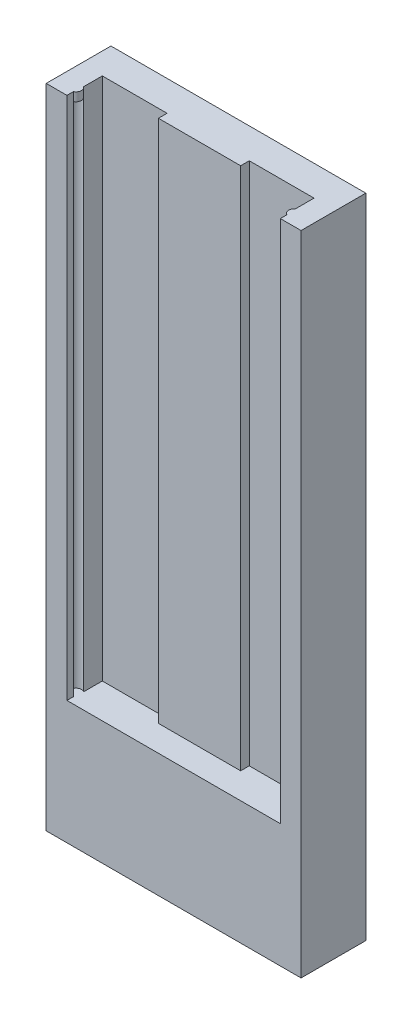
SolidWorks part; units mm, degrees
ref_plane "Front Plane" through (0, 0, 0) normal (0, 0, 1) x (1, 0, 0)
ref_plane "Top Plane" through (0, 0, 0) normal (0, 1, 0) x (1, 0, 0)
ref_plane "Right Plane" through (0, 0, 0) normal (1, 0, 0) x (0, 0, -1)
sketch "Sketch3" plane through (0, 0, 0) normal (0, 1, 0) x (1, 0, 0)
  line L0 (0, 0) -> (0, 38.1)
  line L1 (0, -55) -> (0, 55) construction
  line L2 (0, 38.1) -> (150, 38.1)
  line L3 (150, 38.1) -> (150, 0)
  line L4 (-55, 0) -> (55, 0) construction
  line L5 (150, 0) -> (137.808, 0)
  line L6 (137.808, 0) -> (137.808, 3.81)
  line L7 (12.7, 9.2576) -> (12.7, 20.32)
  line L8 (137.3, 20.32) -> (99.2, 20.32)
  line L9 (99.2, 20.32) -> (99.2, 15.24)
  line L10 (99.2, 15.24) -> (50.8, 15.24)
  line L11 (50.8, 15.24) -> (50.8, 20.32)
  line L12 (50.8, 20.32) -> (12.7, 20.32)
  line L13 (137.3, 9.2576) -> (137.3, 20.32)
  line L14 (12.192, 3.81) -> (12.192, 0)
  line L15 (12.192, 0) -> (0, 0)
  line L16 (12.7, 9.2576) -> (10.8414, 6.6834) construction
  line L17 (10.8414, 6.6834) -> (12.192, 3.81) construction
  line L18 (137.3, 9.2576) -> (139.1586, 6.6834) construction
  line L19 (139.1586, 6.6834) -> (137.808, 3.81) construction
  arc A0 (12.192, 3.81) -> (12.7, 9.2576) centre (10.8414, 6.6834) cw
  arc A1 (137.808, 3.81) -> (137.3, 9.2576) centre (139.1586, 6.6834) ccw
  dimension "D3" = 3.175
  dimension "D1" = 150
  dimension "D2" = 12.7
  dimension "D4" = 3.81
  dimension "D5" = 5.08
  dimension "D6" = 0.508
  dimension "D7" = 12.7
  dimension "D8" = 20.32
  dimension "D9" = 38.1
  dimension "D10" = 38.1
  dimension "D11" = 118.996
extrude "Boss-Extrude1" add sketch "Sketch3" along normal blind 381
sketch "Sketch4" plane through (0, 0, 0) normal (0, 1, 0) x (1, 0, 0)
  circle A0 centre (10.8414, 6.6834) radius 3.175
  circle A1 centre (139.1586, 6.6834) radius 3.175
extrude "Boss-Extrude2" add sketch "Sketch4" along normal blind 5.08
sketch "Sketch5" plane through (0, 381, 0) normal (0, 1, 0) x (1, 0, 0)
  circle A0 centre (139.1586, 6.6834) radius 3.175
  circle A1 centre (10.8414, 6.6834) radius 3.175
extrude "Boss-Extrude3" add sketch "Sketch5" against normal blind 5.08
scale "Scale1" scale about centroid uniform scaling yes scale factor 0.7
sketch "Sketch7" plane through (0, 323.85, 0) normal (0, 1, 0) x (1, 0, 0)
  line L14 (22.5, 7.7527) -> (31.0344, 7.7527)
  line L15 (31.0344, 7.7527) -> (31.0344, 10.4197)
  line L16 (31.39, 14.233) -> (31.39, 21.9767)
  line L17 (31.39, 21.9767) -> (58.06, 21.9767)
  line L18 (58.06, 21.9767) -> (58.06, 18.4207)
  line L19 (58.06, 18.4207) -> (91.94, 18.4207)
  line L20 (91.94, 18.4207) -> (91.94, 21.9767)
  line L21 (91.94, 21.9767) -> (118.61, 21.9767)
  line L22 (118.61, 21.9767) -> (118.61, 14.233)
  line L23 (118.9656, 10.4197) -> (118.9656, 7.7527)
  line L24 (118.9656, 7.7527) -> (127.5, 7.7527)
  line L25 (127.5, 7.7527) -> (127.5, 34.4227)
  line L26 (127.5, 34.4227) -> (22.5, 34.4227)
  line L27 (22.5, 34.4227) -> (22.5, 7.7527)
  line L28 (22.5, 7.7527) -> (31.0344, 7.7527)
  line L29 (31.0344, 7.7527) -> (31.0344, 10.4197)
  line L30 (31.39, 14.233) -> (31.39, 21.9767)
  line L31 (31.39, 21.9767) -> (58.06, 21.9767)
  line L32 (58.06, 21.9767) -> (58.06, 18.4207)
  line L33 (58.06, 18.4207) -> (91.94, 18.4207)
  line L34 (91.94, 18.4207) -> (91.94, 21.9767)
  line L35 (91.94, 21.9767) -> (118.61, 21.9767)
  line L36 (118.61, 21.9767) -> (118.61, 14.233)
  line L37 (118.9656, 10.4197) -> (118.9656, 7.7527)
  line L38 (118.9656, 7.7527) -> (127.5, 7.7527)
  line L39 (127.5, 7.7527) -> (127.5, 34.4227)
  line L40 (127.5, 34.4227) -> (22.5, 34.4227)
  line L41 (22.5, 34.4227) -> (22.5, 7.7527)
  arc A2 (31.0344, 10.4197) -> (31.39, 14.233) centre (30.089, 12.4311) ccw
  arc A3 (118.61, 14.233) -> (118.9656, 10.4197) centre (119.911, 12.4311) ccw
  arc A4 (31.0344, 10.4197) -> (31.39, 14.233) centre (30.089, 12.4311) ccw
  arc A5 (118.61, 14.233) -> (118.9656, 10.4197) centre (119.911, 12.4311) ccw
  dimension "D1" = 0
sketch "Sketch8" plane through (0, 57.15, 0) normal (0, -1, 0) x (1, 0, 0)
  line L0 (22.5, -34.4227) -> (22.5, -7.7527) construction
  line L1 (127.5, -34.4227) -> (22.5, -34.4227)
  line L2 (127.5, -34.4227) -> (127.5, -7.7527)
  line L3 (127.5, -7.7527) -> (22.5, -7.7527)
  line L4 (22.5, -34.4227) -> (22.5, -7.7527)
extrude "Boss-Extrude6" add sketch "Sketch8" against normal blind 50.8
